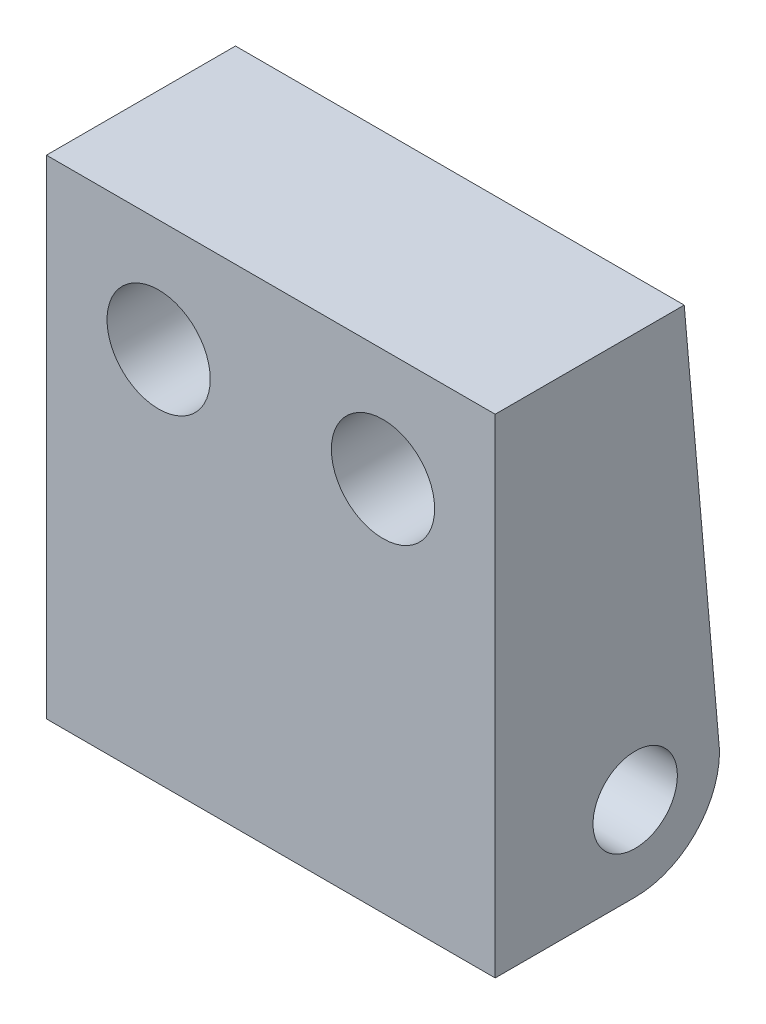
SolidWorks part; units mm, degrees
material "Chrome Stainless Steel"
ref_plane "Front Plane" through (0, 0, 0) normal (0, 0, 1) x (1, 0, 0)
ref_plane "Top Plane" through (0, 0, 0) normal (0, 1, 0) x (1, 0, 0)
ref_plane "Right Plane" through (0, 0, 0) normal (1, 0, 0) x (0, 0, -1)
sketch "Sketch2" plane through (0, 0, 0) normal (0, 0, 1) x (1, 0, 0)
  line L1 (0, 0) -> (12.7, 0)
  line L2 (0, 0) -> (0, 13.8176)
  line L3 (0, 13.8176) -> (12.7, 13.8176)
  line L4 (12.7, 0) -> (12.7, 13.8176)
  dimension "D1" = 12.7
  dimension "D2" = 13.8176
extrude "Boss-Extrude1" add sketch "Sketch2" along normal blind 6.35
sketch "Sketch4" plane through (12.7, 0, 0) normal (1, 0, 0) x (0, 0, -1)
  line L0 (-6.35, 0) -> (0, 0) construction
  line L1 (0, 0) -> (0, 13.8176) construction
  line L2 (0, 2.3876) -> (2.8394, 2.3876)
  line L3 (2.8394, 2.3876) -> (2.8394, -2.4828)
  line L4 (2.8394, -2.4828) -> (-2.3876, -2.4828)
  line L5 (-2.3876, -2.4828) -> (-2.3876, 0)
  arc A0 (-2.3876, 0) -> (0, 2.3876) centre (-2.3876, 2.3876) ccw
  circle A1 centre (-2.3876, 2.3876) radius 1.1938
  dimension "D1" = 4.7752
  dimension "D2" = 2.3876
extrude "Cut-Extrude1" cut sketch "Sketch4" against normal through all
sketch "Sketch7" plane through (12.7, 0, 0) normal (1, 0, 0) x (0, 0, -1)
  line L0 (0, 2.3876) -> (-1.0314, 14.1769)
  line L1 (-1.0314, 14.1769) -> (1.1567, 14.1769)
  line L2 (1.1567, 14.1769) -> (1.1567, 2.3876)
  line L3 (1.1567, 2.3876) -> (0, 2.3876)
  dimension "D1" = 5
extrude "Cut-Extrude2" cut sketch "Sketch7" against normal through all
sketch "Sketch8" plane through (0, 0, 6.35) normal (0, 0, 1) x (1, 0, 0)
  line L0 (0, 13.8176) -> (0, 0) construction
  line L1 (12.7, 13.8176) -> (0, 13.8176) construction
  line L2 (6.35, 13.8176) -> (6.35, 0) construction
  line L3 (0, 0) -> (12.7, 0) construction
  circle A0 centre (3.175, 10.6426) radius 3.175 construction
  circle A1 centre (3.175, 10.6426) radius 2.7813 construction
  circle A2 centre (3.175, 10.6426) radius 1.4605
  circle A3 centre (9.525, 10.6426) radius 2.7813 construction
  circle A4 centre (9.525, 10.6426) radius 3.175 construction
  circle A5 centre (9.525, 10.6426) radius 1.4605
  dimension "D1" = 6.35
  dimension "D2" = 5.5626
  dimension "D3" = 2.921
extrude "Cut-Extrude3" cut sketch "Sketch8" against normal through all
ref_plane "Plane1" through (0, 0, 1.27) normal (0, 0, 1) x (1, 0, 0)
sketch "Sketch9" plane through (0, 0, 1.27) normal (0, 0, 1) x (1, 0, 0)
  circle A0 centre (3.175, 10.6426) radius 2.7813 construction
  circle A1 centre (9.525, 10.6426) radius 2.7813 construction
  circle A2 centre (3.175, 10.6426) radius 2.7813
  circle A3 centre (9.525, 10.6426) radius 2.7813
extrude "Cut-Extrude4" cut sketch "Sketch9" against normal through all
